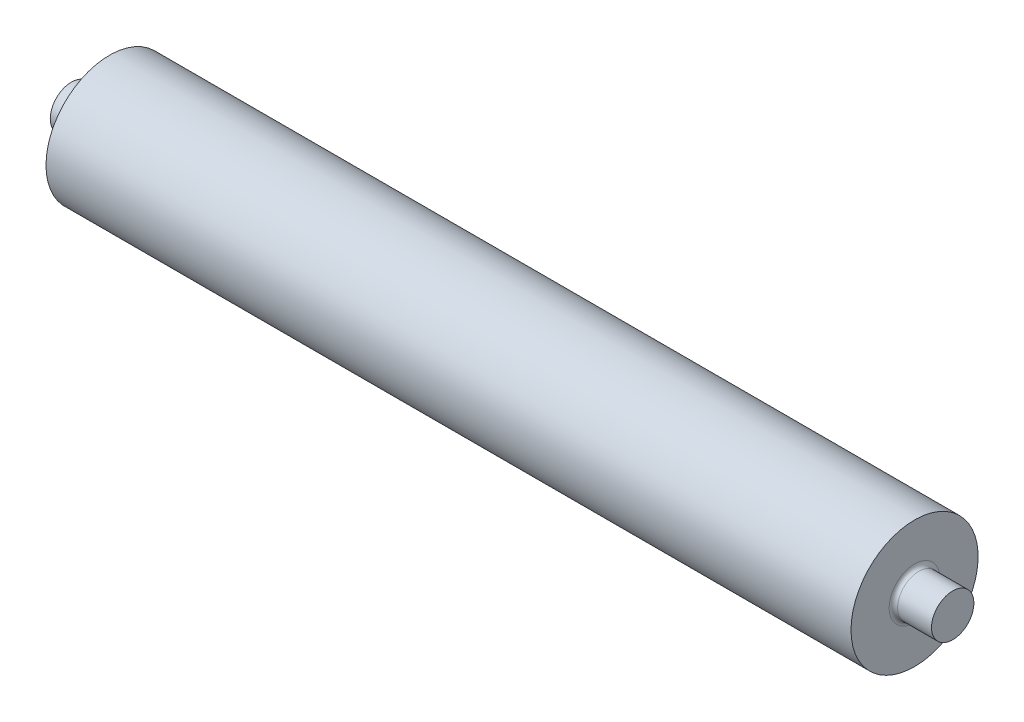
SolidWorks part; units mm, degrees
ref_plane "Front Plane" through (0, 0, 0) normal (0, 0, 1) x (1, 0, 0)
ref_plane "Top Plane" through (0, 0, 0) normal (0, 1, 0) x (1, 0, 0)
ref_plane "Right Plane" through (0, 0, 0) normal (1, 0, 0) x (0, 0, -1)
sketch "Sketch1" plane through (0, 0, 0) normal (0, 0, 1) x (1, 0, 0)
  line L0 (-1040, 0) -> (1040, 0)
  line L1 (-1040, 0) -> (-1040, 50)
  line L2 (-1040, 50) -> (-950, 50)
  line L3 (-950, 50) -> (-950, 150)
  line L4 (-950, 150) -> (950, 150)
  line L5 (0, 0) -> (0, 874.9438) construction
  line L6 (950, 50) -> (950, 150)
  line L7 (1040, 50) -> (950, 50)
  line L8 (1040, 0) -> (1040, 50)
  point P4 (0, 0)
  point P12 (0, 150)
  dimension "D1" = 2080
  dimension "D2" = 50
  dimension "D3" = 150
  dimension "D4" = 950
revolve "Revolve1" add sketch "Sketch1" angle 360 about L0
fillet "Fillet1" radius 10 2 edges at (-950, 0, 50) (950, 0, 50)
